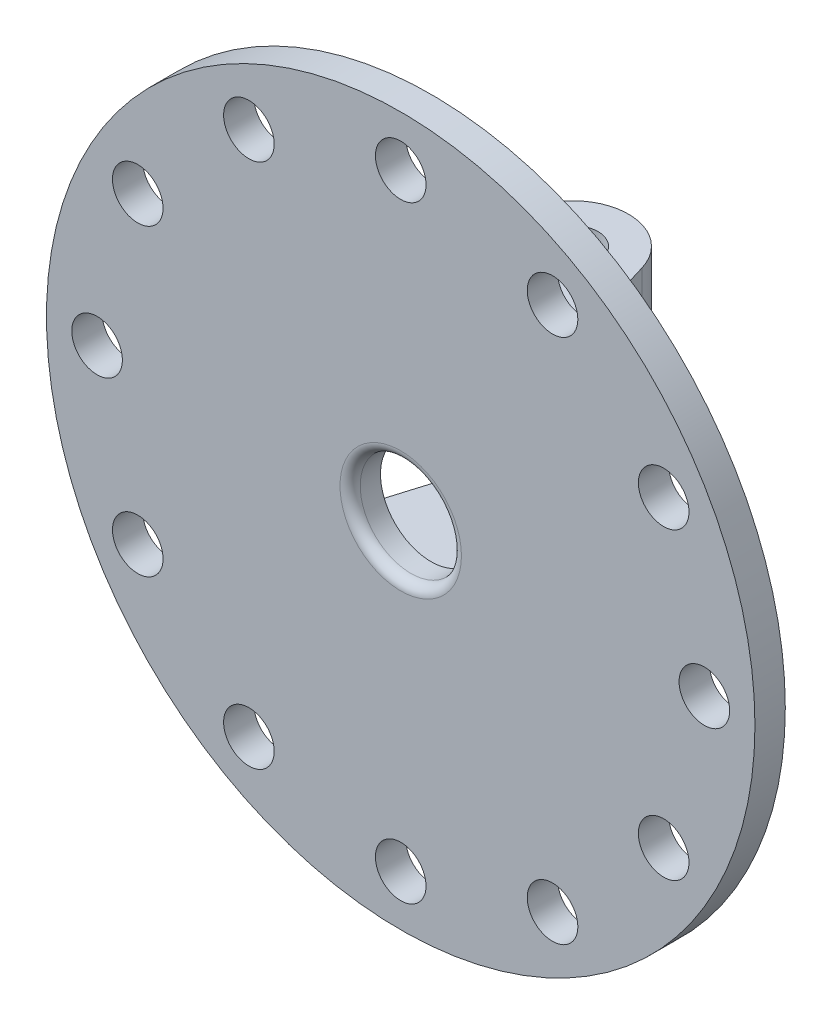
SolidWorks part; units mm, degrees
ref_plane "정면" through (0, 0, 0) normal (0, 0, 1) x (1, 0, 0)
ref_plane "윗면" through (0, 0, 0) normal (0, 1, 0) x (1, 0, 0)
ref_plane "우측면" through (0, 0, 0) normal (1, 0, 0) x (0, 0, -1)
sketch "스케치1" plane through (0, 0, 0) normal (0, 0, 1) x (1, 0, 0)
  line L0 (0, 65.3097) -> (0, -65.3097) construction
  line L1 (-109.2501, 0) -> (109.2501, 0) construction
  line L2 (15, 25.9808) -> (0, 0) construction
  circle A0 centre (0, 0) radius 5
  circle A1 centre (0, 0) radius 30 construction
  circle A2 centre (0, 0) radius 35
  circle A3 centre (0, 30) radius 2.5
  circle A18 centre (15, 25.9808) radius 2.5
  circle A19 centre (25.9808, 15) radius 2.5
  circle A20 centre (30, 0) radius 2.5
  circle A21 centre (25.9808, -15) radius 2.5
  circle A22 centre (15, -25.9808) radius 2.5
  circle A23 centre (0, -30) radius 2.5
  circle A24 centre (-15, -25.9808) radius 2.5
  circle A25 centre (-25.9808, -15) radius 2.5
  circle A26 centre (-30, 0) radius 2.5
  circle A27 centre (-25.9808, 15) radius 2.5
  circle A28 centre (-15, 25.9808) radius 2.5
  point P5 (0, 0)
  point P6 (0, 0)
  point P39 (0, 0)
  point P44 (0, 0)
  dimension "D1" = 10
  dimension "D2" = 60
  dimension "D3" = 70
  dimension "D4" = 5
  dimension "D6" = 30
  dimension "D5" = 12
sketch "스케치3" plane through (0, 0, 0) normal (0, 1, 0) x (1, 0, 0)
  line L0 (-46.8932, 0) -> (33.9265, 0) construction
  line L1 (-109.2501, 0) -> (109.2501, 0) construction
  line L2 (27.5, 0) -> (32.5, 0) construction
  line L3 (0, -29.8322) -> (0, 29.8322) construction
  line L4 (-10, 0) -> (10, 0)
  line L5 (0, 0) -> (0, 14) construction
  line L6 (-10, 0) -> (-5.2626, 15.5983)
  line L7 (10, 0) -> (5.2626, 15.5983)
  circle A0 centre (0, 14) radius 2.5
  arc A2 (5.2626, 15.5983) -> (-5.2626, 15.5983) centre (0, 14) ccw
  point P6 (0, 0)
  point P10 (0, 0)
  dimension "D3" = 5
  dimension "D4" = 5.5
  dimension "D1" = 20
  dimension "D2" = 14
sketch "스케치4" plane through (0, 0, 0) normal (1, 0, 0) x (0, 0, -1)
  line L0 (0, -6) -> (0, 6)
  line L1 (0, 65.3097) -> (0, -65.3097) construction
  line L5 (0, -6) -> (25, -6)
  line L6 (25, -6) -> (25, 6)
  line L7 (25, 6) -> (0, 6)
  point P4 (0, 0)
  dimension "D1" = 12
  dimension "D2" = 25
extrude "보스-돌출1" add sketch "스케치3" along normal mid plane 30
extrude "컷-돌출1" cut sketch "스케치4" against normal mid plane 30
extrude "보스-돌출2" add sketch "스케치1" along normal blind 3
fillet "필렛1" radius 1 1 edges at (5, 0, 3)
